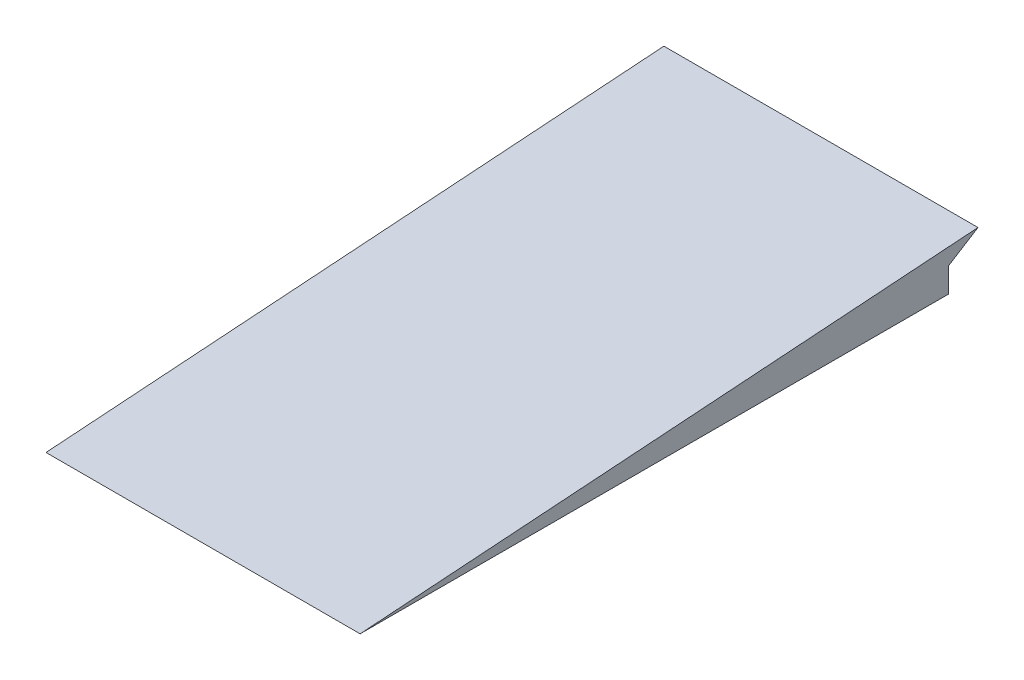
SolidWorks part; units mm, degrees
material "Pine"
ref_plane "Front" through (0, 0, 0) normal (0, 0, 1) x (1, 0, 0)
ref_plane "Top" through (0, 0, 0) normal (0, 1, 0) x (1, 0, 0)
ref_plane "Right" through (0, 0, 0) normal (1, 0, 0) x (0, 0, -1)
sketch "Sketch1" plane through (0, 0, 0) normal (1, 0, 0) x (0, 0, -1)
  line L0 (0, 0) -> (3045.353, 127)
  line L1 (3045.353, 127) -> (3045.353, 0)
  line L2 (3045.353, 0) -> (0, 0)
  dimension "D1" = 127
  dimension "D2" = 3048
extrude "Boss-Extrude1" add sketch "Sketch1" along normal mid plane 1625.6
sketch "Sketch2" plane through (812.8, 0, 0) normal (1, 0, 0) x (0, 0, -1)
  line L0 (3045.353, 127) -> (3197.753, 222.25)
  line L1 (3197.753, 222.25) -> (0, 0)
  line L2 (3045.353, 127) -> (0, 0)
  dimension "D1" = 152.4
  dimension "D2" = 95.25
extrude "Boss-Extrude2" add sketch "Sketch2" against normal up to surface (1625.6 mm away) up to face at (-812.8, 42.3333, -2030.2353)
